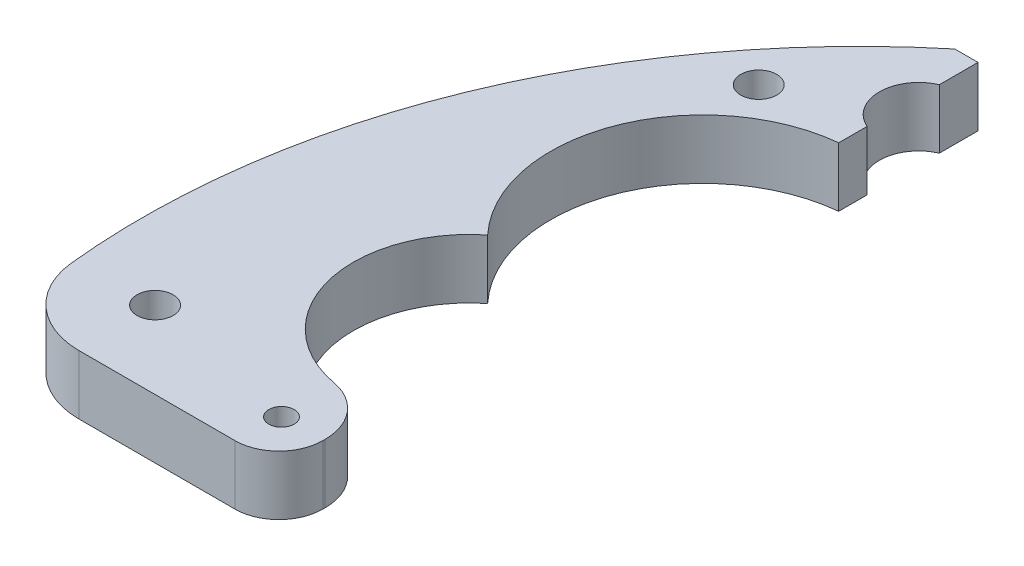
SolidWorks part; units mm, degrees
ref_plane "Front Plane" through (0, 0, 0) normal (0, 0, 1) x (1, 0, 0)
ref_plane "Top Plane" through (0, 0, 0) normal (0, 1, 0) x (1, 0, 0)
ref_plane "Right Plane" through (0, 0, 0) normal (1, 0, 0) x (0, 0, -1)
sketch "Sketch1" plane through (0, 0, 0) normal (0, 1, 0) x (1, 0, 0)
  line L0 (30.3798, 69.405) -> (32.6658, 69.405)
  line L1 (32.6658, 69.405) -> (32.6658, 0.571)
  line L5 (32.6658, 0.571) -> (6.2498, 0.571)
  arc A0 (6.2498, 0.571) -> (30.3798, 69.405) centre (75.3749, 14.9854) cw
  point P4 (30.3798, 69.405)
  dimension "D1" = 26.416
  dimension "D2" = 68.834
  dimension "D3" = 2.286
extrude "Boss-Extrude1" add sketch "Sketch1" along normal blind 5.842
sketch "Sketch2" plane through (0, 5.842, 0) normal (0, 1, 0) x (1, 0, 0)
  line L0 (32.6658, 0.571) -> (32.6658, 69.405) construction
  line L1 (32.6658, 65.595) -> (32.6658, 58.483)
  arc A0 (32.6658, 58.483) -> (32.6658, 65.595) centre (34.1898, 62.039) cw
  point P0 (32.6658, 65.595)
  point P1 (32.6658, 58.483)
  dimension "D3" = 1.524
  dimension "D1" = 3.81
  dimension "D2" = 7.112
extrude "Cut-Extrude1" cut sketch "Sketch2" against normal through all
sketch "Sketch7" plane through (0, 5.842, 0) normal (0, 1, 0) x (1, 0, 0)
  line L1 (32.6658, 0.571) -> (32.6658, 58.483) construction
  line L2 (34.1898, 0.571) -> (34.1898, 58.483)
  line L3 (34.1898, 0.571) -> (34.1898, 58.483) construction
  line L4 (32.6658, 55.689) -> (32.6658, 25.8724)
  arc A0 (32.6658, 55.689) -> (32.6658, 25.8724) centre (34.1898, 40.7807) ccw
  dimension "D2" = 2.794
  dimension "D3" = 14.986
  dimension "D1" = 1.524
extrude "Cut-Extrude2" cut sketch "Sketch7" against normal through all
sketch "Sketch8" plane through (0, 5.842, 0) normal (0, 1, 0) x (1, 0, 0)
  line L2 (32.6658, 30.543) -> (0, 30.543) construction
  line L3 (32.6658, 30.543) -> (30.3798, 30.543)
  line L4 (32.6658, 30.543) -> (30.3798, 30.543) construction
  line L8 (30.3798, 0.571) -> (30.3798, 25.8724)
  line L9 (30.3798, 0.571) -> (30.3798, 25.8724) construction
  circle A0 centre (30.3798, 21.6126) radius 11.43
  arc A1 (32.6658, 55.689) -> (32.6658, 25.8724) centre (34.1898, 40.7807) ccw construction
  point P4 (23.2459, 30.543)
  point P13 (32.6658, 9.969)
  dimension "D1" = 2.286
  dimension "D2" = 22.86
  dimension "D3" = 38.862
extrude "Cut-Extrude3" cut sketch "Sketch8" against normal through all
fillet "Fillet1" radius 7.874 1 edges at (6.2498, 2.921, -0.571)
fillet "Fillet2" radius 4.318 1 edges at (32.6658, 2.921, -0.571)
fillet "Fillet4" radius 5.334 1 edges at (32.6658, 2.921, -10.4135)
sketch "Sketch9" plane through (0, 5.842, 0) normal (0, 1, 0) x (1, 0, 0)
  circle A0 centre (23.7758, 56.705) radius 1.7748
  dimension "D1" = 8.89
  dimension "D2" = 1.016
extrude "Cut-Extrude4" cut sketch "Sketch9" against normal through all
sketch "Sketch10" plane through (0, 5.842, 0) normal (0, 1, 0) x (1, 0, 0)
  circle A0 centre (28.6018, 4.889) radius 1.25
  dimension "D1" = 2.5
  dimension "D2" = 4.064
  dimension "D3" = 4.318
extrude "Cut-Extrude5" cut sketch "Sketch10" against normal through all
sketch "Sketch11" plane through (0, 5.842, 0) normal (0, 1, 0) x (1, 0, 0)
  line L0 (12.9788, 0.571) -> (28.3478, 0.571) construction
  circle A0 centre (12.8538, 8.191) radius 1.778
  dimension "D1" = 3.556
  dimension "D2" = 19.812
  dimension "D3" = 7.62
extrude "Cut-Extrude6" cut sketch "Sketch11" against normal through all
